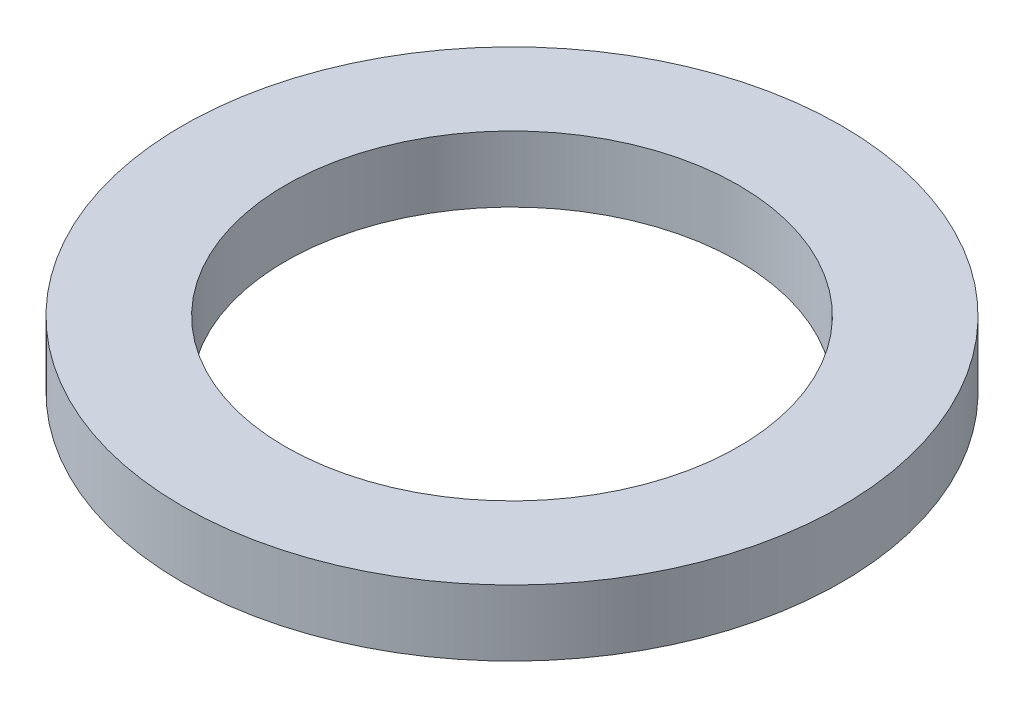
SolidWorks part; units mm, degrees
material "Stainless Steel (ferritic)"
ref_plane "Front Plane" through (0, 0, 0) normal (0, 0, 1) x (1, 0, 0)
ref_plane "Top Plane" through (0, 0, 0) normal (0, 1, 0) x (1, 0, 0)
ref_plane "Right Plane" through (0, 0, 0) normal (1, 0, 0) x (0, 0, -1)
sketch "Sketch1" plane through (0, 0, 0) normal (0, 1, 0) x (1, 0, 0)
  circle A0 centre (0, 0) radius 11
  circle A1 centre (0, 0) radius 16
  dimension "D1" = 22
  dimension "D2" = 5
extrude "Boss-Extrude1" add sketch "Sketch1" along normal mid plane 3.2
